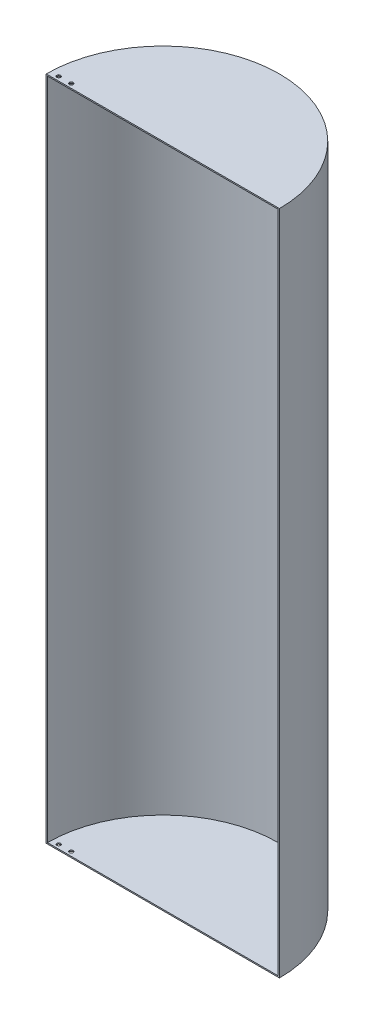
SolidWorks part; units mm, degrees
material "AISI 316 Stainless Steel Sheet (SS)"
ref_plane "Front Plane" through (0, 0, 0) normal (0, 0, 1) x (1, 0, 0)
ref_plane "Top Plane" through (0, 0, 0) normal (0, 1, 0) x (1, 0, 0)
ref_plane "Right Plane" through (0, 0, 0) normal (1, 0, 0) x (0, 0, -1)
sketch "Sketch1" plane through (0, 0, 0) normal (0, 1, 0) x (1, 0, 0)
  line L0 (-140, 0) -> (140, 0)
  arc A0 (140, 0) -> (-140, 0) centre (0, 0) ccw
  dimension "D1" = 280
extrude "Boss-Extrude1" add sketch "Sketch1" along normal blind 800
shell "Shell1" thickness 1.5
hole_wizard "M4 Clearance Hole1" positions "Sketch2" profile "Sketch3" hole size "M4" standard "JIS" end condition through all
sketch "Sketch2" plane through (0, 800, 0) normal (0, 1, 0) x (1, 0, 0)
  arc A0 (140, 0) -> (-140, 0) centre (0, 0) ccw construction
  point P0 (-130, 5)
  point P2 (-115, 5)
  dimension "D1" = 5
  dimension "D2" = 10
  dimension "D3" = 15
sketch "Sketch3" plane through (-130, 800, -5) normal (1, 0, 0) x (0, 0, 1)
  line L0 (0, 0) -> (0, 800)
  line L1 (0, 800) -> (2.25, 800)
  line L2 (2.25, 800) -> (2.25, 0.021)
  line L3 (2.25, 0.021) -> (2.275, 0)
  line L5 (2.275, 0) -> (0, 0)
  line L6 (-2.25, 0.021) -> (-2.275, 0) construction
  line L11 (0, -6.35) -> (0, 107.95) construction
  dimension "Thru Hole Dia." = 4.5
  dimension "Thru Hole Depth" = 800
  dimension "Near C'Sink Dia." = 4.55
  dimension "Near C'Sink Angle" = 100
